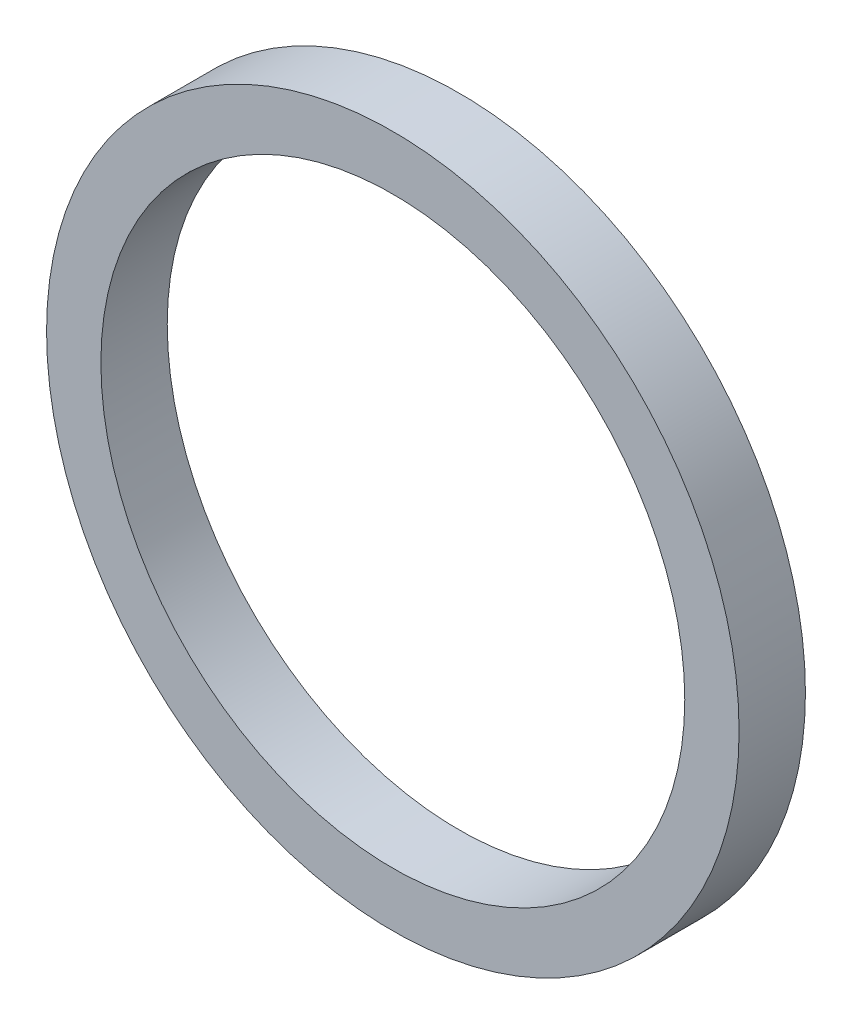
SolidWorks part; units mm, degrees
ref_plane "Front Plane" through (0, 0, 0) normal (0, 0, 1) x (1, 0, 0)
ref_plane "Top Plane" through (0, 0, 0) normal (0, 1, 0) x (1, 0, 0)
ref_plane "Right Plane" through (0, 0, 0) normal (1, 0, 0) x (0, 0, -1)
sketch "Sketch1" plane through (0, 0, 0) normal (1, 0, 0) x (0, 0, -1)
  line L0 (0, 0) -> (-7.5927, 0) construction
  line L1 (-4, 20.875) -> (-4, 17.6)
  line L4 (-4, 17.6) -> (0, 17.6)
  line L5 (0, 17.6) -> (0, 20.875)
  line L6 (0, 20.875) -> (-4, 20.875)
  point P6 (-3.4755, 3.9075)
  point P9 (-3.2728, 1.9439)
  dimension "D1" = 4
  dimension "D2" = 41.75
  dimension "D3" = 35.2
revolve "Revolve1" add sketch "Sketch1" angle 360 about L0
